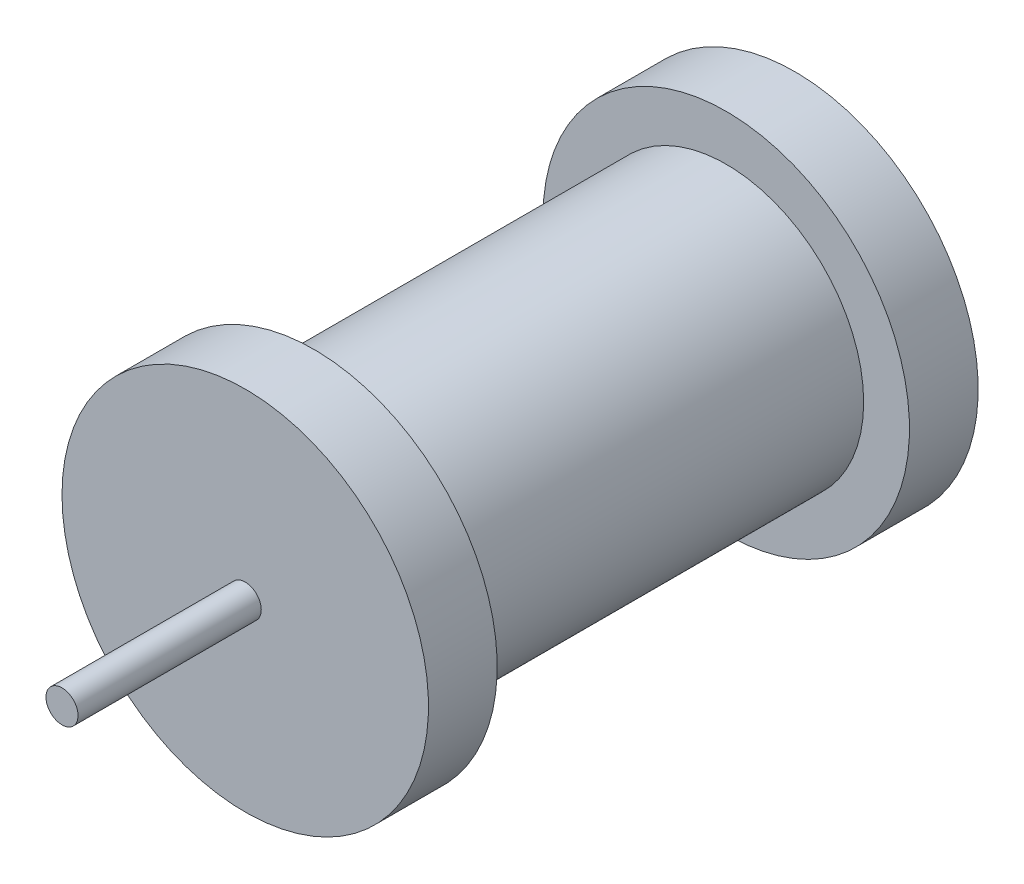
SolidWorks part; units mm, degrees
ref_plane "Front Plane" through (0, 0, 0) normal (0, 0, 1) x (1, 0, 0)
ref_plane "Top Plane" through (0, 0, 0) normal (0, 1, 0) x (1, 0, 0)
ref_plane "Right Plane" through (0, 0, 0) normal (1, 0, 0) x (0, 0, -1)
sketch "Sketch1" plane through (0, 0, 0) normal (0, 1, 0) x (1, 0, 0)
  line L0 (0, -8.0407) -> (0, 8.7061) construction
  line L1 (15, 30) -> (20, 30)
  line L2 (20, 30) -> (20, 22.5)
  line L3 (20, 22.5) -> (15, 22.5)
  line L4 (15, 22.5) -> (15, -22.5)
  line L5 (15, 30) -> (0, 30)
  line L6 (15, -30) -> (0, -30)
  line L7 (20, -22.5) -> (15, -22.5)
  line L8 (20.2033, 0) -> (-21.0166, 0) construction
  line L9 (20, -30) -> (20, -22.5)
  line L10 (15, -30) -> (20, -30)
  line L11 (0, 30) -> (0, -30)
  point P14 (15, 0)
  dimension "D1" = 15
  dimension "D2" = 7.5
  dimension "D3" = 30
  dimension "D4" = 5
revolve "Revolve1" add sketch "Sketch1" angle 360 about L11
sketch "Sketch2" plane through (0, 0, 0) normal (0, 1, 0) x (1, 0, 0)
  line L0 (0, -50) -> (1.75, -50)
  line L1 (0, -200008.0407) -> (0, 200008.7061) construction
  line L2 (1.75, -50) -> (1.75, -30)
  line L3 (15, -30) -> (0, -30) construction
  line L4 (1.75, -30) -> (0, -30)
  line L5 (0, -30) -> (0, -50)
  dimension "D1" = 20
  dimension "D2" = 1.75
revolve "Revolve2" add sketch "Sketch2" angle 360 about L0
